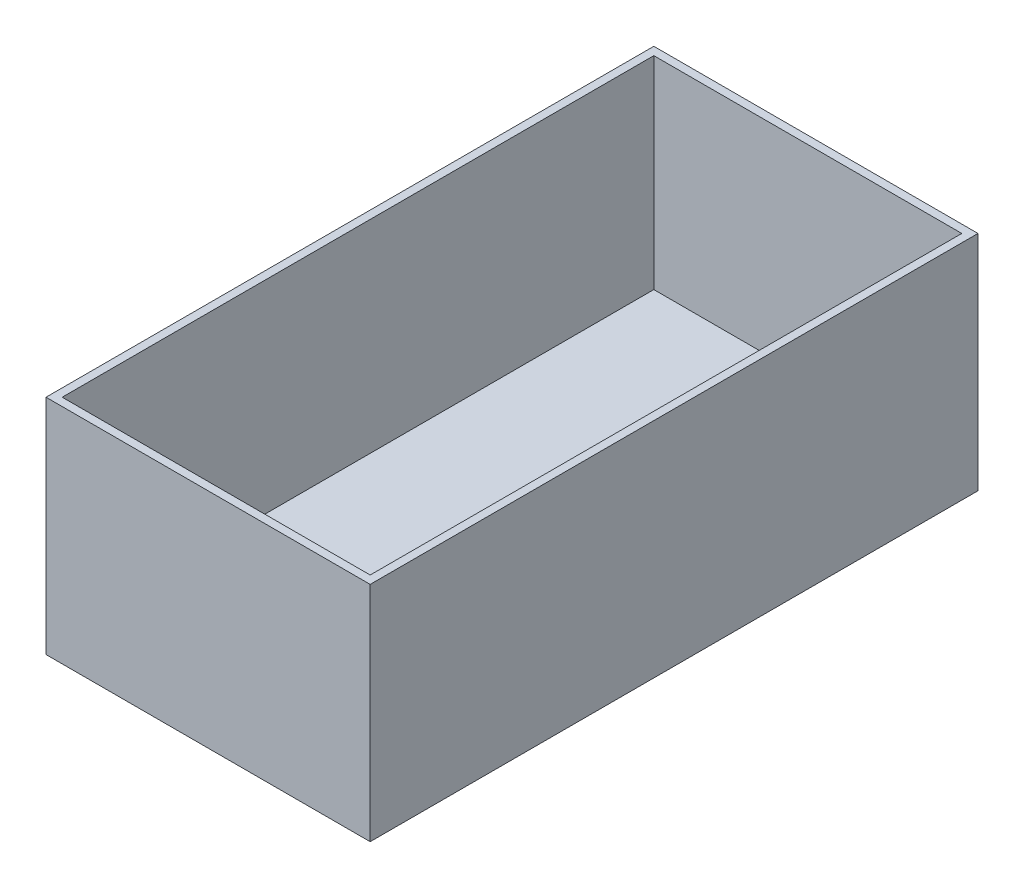
SolidWorks part; units mm, degrees
ref_plane "Front Plane" through (0, 0, 0) normal (0, 0, 1) x (1, 0, 0)
ref_plane "Top Plane" through (0, 0, 0) normal (0, 1, 0) x (1, 0, 0)
ref_plane "Right Plane" through (0, 0, 0) normal (1, 0, 0) x (0, 0, -1)
sketch "Sketch1" plane through (0, 0, 0) normal (0, 1, 0) x (1, 0, 0)
  line L1 (-40, 75) -> (40, 75)
  line L2 (-40, 75) -> (-40, -75)
  line L3 (-40, -75) -> (40, -75)
  line L4 (40, 75) -> (40, -75)
  line L5 (-40, 75) -> (40, -75) construction
  line L6 (-40, -75) -> (40, 75) construction
  point P0 (0, 0)
  dimension "D1" = 150
  dimension "D2" = 80
extrude "Boss-Extrude1" add sketch "Sketch1" along normal blind 5
sketch "Sketch2" plane through (0, 5, 0) normal (0, 1, 0) x (1, 0, 0)
  line L0 (-40, 75) -> (40, 75)
  line L1 (40, 75) -> (40, -75)
  line L2 (40, -75) -> (-40, -75)
  line L3 (-40, -75) -> (-40, 75)
  line L4 (-38, 73) -> (-38, -73)
  line L5 (-38, -73) -> (38, -73)
  line L6 (38, -73) -> (38, 73)
  line L7 (38, 73) -> (-38, 73)
  point P11 (0, 75)
  dimension "D1" = 2
  dimension "D2" = 2
  dimension "D3" = 2
  dimension "D4" = 2
extrude "Boss-Extrude2" add sketch "Sketch2" along normal blind 50
